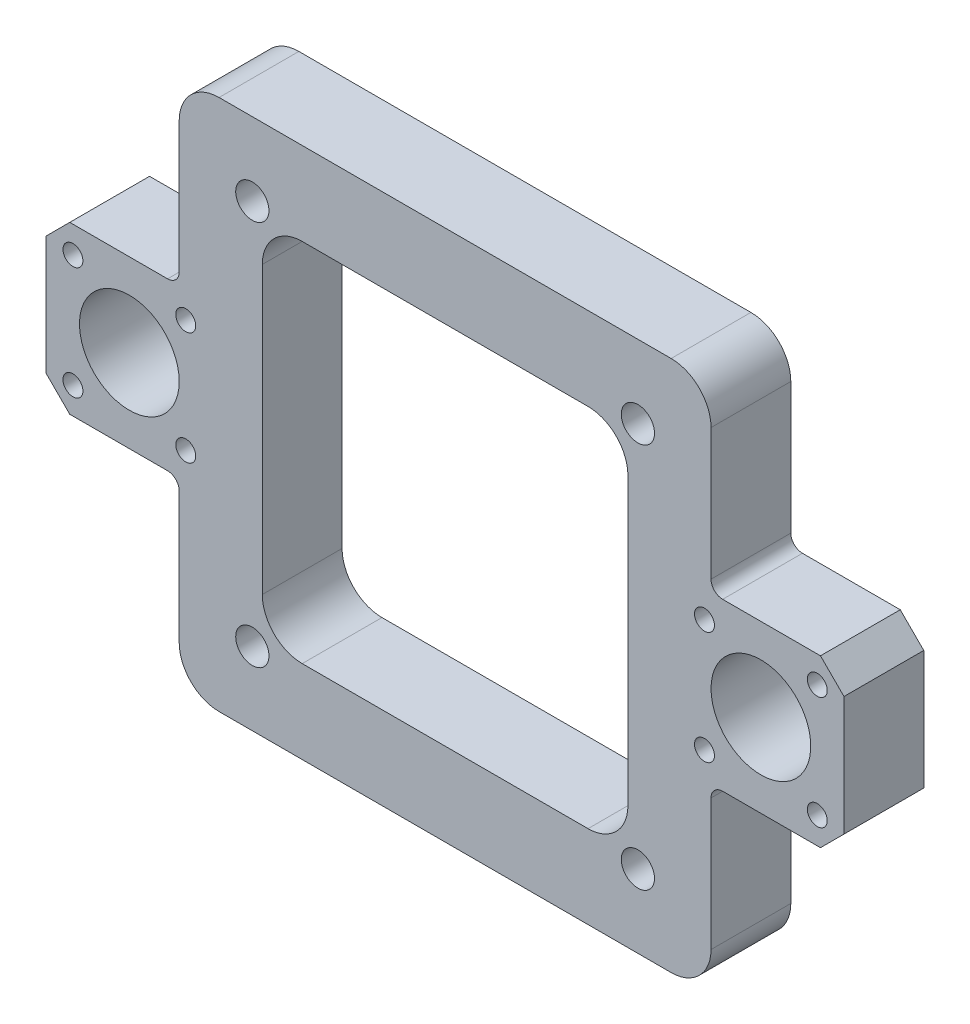
SolidWorks part; units mm, degrees
ref_plane "Front Plane" through (0, 0, 0) normal (0, 0, 1) x (1, 0, 0)
ref_plane "Top Plane" through (0, 0, 0) normal (0, 1, 0) x (1, 0, 0)
ref_plane "Right Plane" through (0, 0, 0) normal (1, 0, 0) x (0, 0, -1)
sketch "Sketch1" plane through (0, 0, 0) normal (0, 0, 1) x (1, 0, 0)
  line L0 (-47.5, 0) -> (47.5, 0) construction
  line L1 (0, 0) -> (0, 17.3262) construction
  line L2 (-56.4645, 12.5) -> (-41.75, 12.5)
  line L3 (-40, 14.25) -> (-40, 34)
  line L12 (-56.4645, 12.5) -> (-60, 8.9645)
  line L13 (-60, 8.9645) -> (-60, -8.9645)
  line L14 (34, 40) -> (-34, 40)
  line L15 (60, 8.9645) -> (60, -8.9645)
  line L16 (56.4645, 12.5) -> (60, 8.9645)
  line L17 (56.4645, 12.5) -> (41.75, 12.5)
  line L18 (40, 14.25) -> (40, 34)
  line L19 (-56.4645, -12.5) -> (-60, -8.9645)
  line L20 (-56.4645, -12.5) -> (-41.75, -12.5)
  line L21 (-40, -14.25) -> (-40, -34)
  line L22 (34, -40) -> (-34, -40)
  line L23 (40, -14.25) -> (40, -34)
  line L24 (56.4645, -12.5) -> (41.75, -12.5)
  line L25 (56.4645, -12.5) -> (60, -8.9645)
  line L26 (-55.9853, 8.4853) -> (-39.0147, -8.4853) construction
  line L27 (-55.9853, -8.4853) -> (-39.0147, 8.4853) construction
  circle A0 centre (-47.5, 0) radius 7.5
  arc A12 (-41.75, 12.5) -> (-40, 14.25) centre (-41.75, 14.25) ccw
  arc A13 (-40, 34) -> (-34, 40) centre (-34, 34) cw
  arc A14 (41.75, 12.5) -> (40, 14.25) centre (41.75, 14.25) cw
  arc A15 (40, 34) -> (34, 40) centre (34, 34) ccw
  arc A16 (-41.75, -12.5) -> (-40, -14.25) centre (-41.75, -14.25) cw
  arc A17 (-40, -34) -> (-34, -40) centre (-34, -34) ccw
  arc A18 (40, -34) -> (34, -40) centre (34, -34) cw
  arc A19 (41.75, -12.5) -> (40, -14.25) centre (41.75, -14.25) ccw
  circle A20 centre (47.5, 0) radius 7.5
  circle A21 centre (-55.9853, 8.4853) radius 1.5
  circle A22 centre (-39.0147, -8.4853) radius 1.5
  circle A23 centre (-39.0147, 8.4853) radius 1.5
  circle A24 centre (-55.9853, -8.4853) radius 1.5
  circle A25 centre (39.0147, -8.4853) radius 1.5
  circle A26 centre (55.9853, -8.4853) radius 1.5
  circle A27 centre (55.9853, 8.4853) radius 1.5
  circle A28 centre (39.0147, 8.4853) radius 1.5
  circle A29 centre (-29, 29) radius 2.5
  circle A33 centre (29, 29) radius 2.5
  circle A34 centre (29, -29) radius 2.5
  circle A35 centre (-29, -29) radius 2.5
  point P28 (0, 40)
  point P29 (-60, 0)
  point P44 (60, 0)
  dimension "D2" = 15
  dimension "D3" = 25
  dimension "D6" = 1.75
  dimension "D11" = 3
  dimension "D13" = 6
  dimension "D15" = 5
  dimension "D1" = 95
  dimension "D4" = 120
  dimension "D5" = 40
  dimension "D7" = 135
  dimension "D8" = 80
  dimension "D9" = 5
  dimension "D10" = 24
  dimension "D12" = 135
  dimension "D14" = 58
  dimension "D16" = 58
extrude "Boss-Extrude1" add sketch "Sketch1" along normal blind 12
sketch "Sketch2" plane through (0, 0, 12) normal (0, 0, 1) x (1, 0, 0)
  line L0 (-21.5, 21.5) -> (21.5, -21.5) construction
  line L1 (-21.5, 27.5) -> (21.5, 27.5)
  line L2 (-27.5, 21.5) -> (-27.5, -21.5)
  line L3 (-21.5, -27.5) -> (21.5, -27.5)
  line L4 (27.5, 21.5) -> (27.5, -21.5)
  arc A0 (-27.5, -21.5) -> (-21.5, -27.5) centre (-21.5, -21.5) ccw
  arc A1 (21.5, -27.5) -> (27.5, -21.5) centre (21.5, -21.5) ccw
  arc A2 (27.5, 21.5) -> (21.5, 27.5) centre (21.5, 21.5) ccw
  arc A3 (-21.5, 27.5) -> (-27.5, 21.5) centre (-21.5, 21.5) ccw
  dimension "D1" = 6
  dimension "D2" = 55
extrude "Cut-Extrude1" cut sketch "Sketch2" against normal through all both and the other way through all
